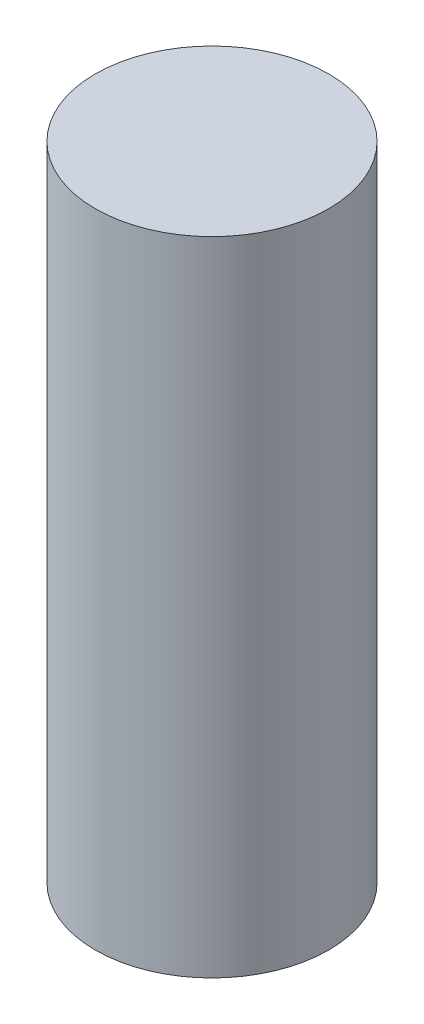
SolidWorks part; units mm, degrees
ref_plane "Front Plane" through (0, 0, 0) normal (0, 0, 1) x (1, 0, 0)
ref_plane "Top Plane" through (0, 0, 0) normal (0, 1, 0) x (1, 0, 0)
ref_plane "Right Plane" through (0, 0, 0) normal (1, 0, 0) x (0, 0, -1)
sketch "Sketch1" plane through (0, 0, 0) normal (0, 1, 0) x (1, 0, 0)
  circle A0 centre (0, 0) radius 20.32
  dimension "D1" = 40.64
extrude "Boss-Extrude1" add sketch "Sketch1" along normal blind 111.76
